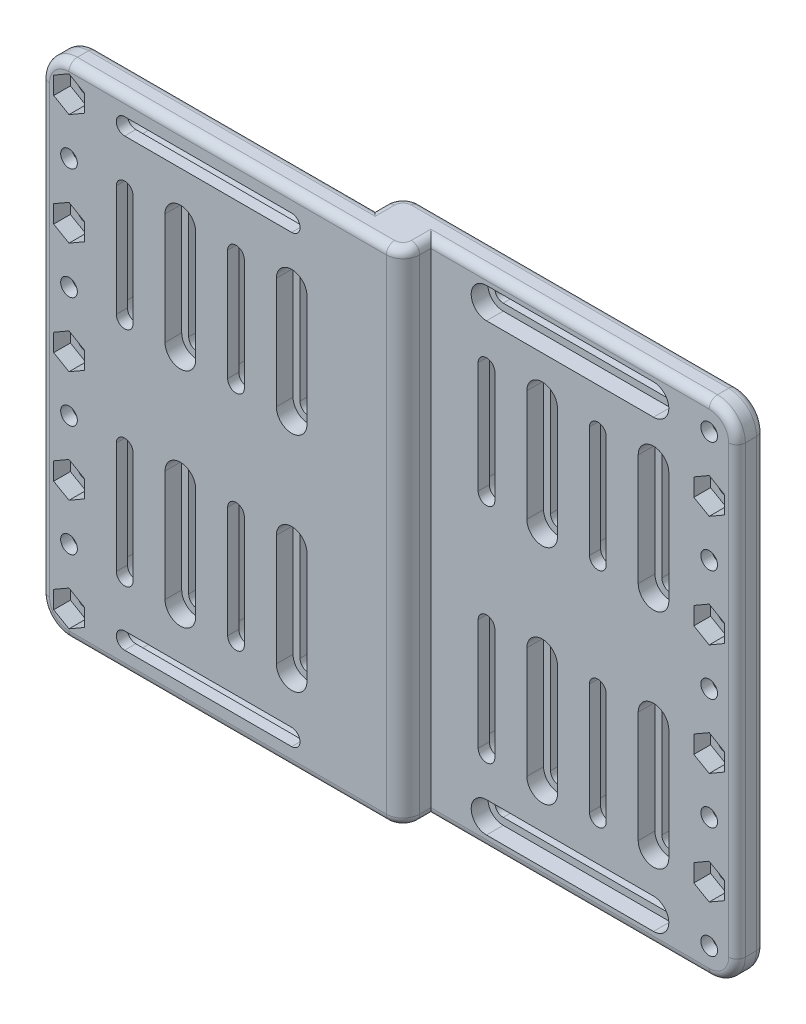
SolidWorks part; units mm, degrees
ref_plane "Front Plane" through (0, 0, 0) normal (0, 0, 1) x (1, 0, 0)
ref_plane "Top Plane" through (0, 0, 0) normal (0, 1, 0) x (1, 0, 0)
ref_plane "Right Plane" through (0, 0, 0) normal (1, 0, 0) x (0, 0, -1)
sketch "草图1" plane through (0, 0, 0) normal (0, 0, 1) x (1, 0, 0)
  line L2 (0, 45) -> (0, -45) construction
  circle A0 centre (0, 0) radius 45 construction
  dimension "D1" = 90
sketch "草图2" plane through (0, 0, 0) normal (0, 0, 1) x (1, 0, 0)
  line L0 (0, 45) -> (5, 45)
  line L1 (0, 45) -> (-60, 45)
  line L2 (0, 45) -> (0, -45) construction
  line L3 (0, -45) -> (-60, -45)
  line L4 (-60, 45) -> (-60, -45)
  line L5 (5, 45) -> (5, -45)
  line L6 (5, -45) -> (0, -45)
  dimension "D1" = 60
  dimension "D2" = 5
extrude "凸台-拉伸2" add sketch "草图2" along normal blind 5
sketch "草图3" plane through (0, 0, 0) normal (0, 0, -1) x (-1, 0, 0)
  line L0 (0, 45) -> (5, 45)
  line L1 (0, 45) -> (-60, 45)
  line L2 (0, 45) -> (0, -45) construction
  line L3 (0, -45) -> (-60, -45)
  line L4 (-60, 45) -> (-60, -45)
  line L5 (-5, 45) -> (60, 45) construction
  line L6 (5, 45) -> (5, -45)
  line L7 (60, -45) -> (-5, -45) construction
  line L8 (5, -45) -> (0, -45)
  dimension "D1" = 60
  dimension "D2" = 5
extrude "凸台-拉伸3" add sketch "草图3" along normal blind 5
sketch "草图4" plane through (0, 0, -5) normal (0, 0, -1) x (-1, 0, 0)
  line L0 (-60, 45) -> (-60, -45) construction
  circle A0 centre (-55, 0) radius 1.5
  dimension "D2" = 3
  dimension "D1" = 5
sketch "草图5" plane through (0, 0, -5) normal (0, 0, -1) x (-1, 0, 0)
  line L1 (-55, -3.1754) -> (-52.25, -1.5877)
  line L2 (-52.25, -1.5877) -> (-52.25, 1.5877)
  line L3 (-52.25, 1.5877) -> (-55, 3.1754)
  line L4 (-55, 3.1754) -> (-57.75, 1.5877)
  line L5 (-57.75, 1.5877) -> (-57.75, -1.5877)
  line L6 (-57.75, -1.5877) -> (-55, -3.1754)
  circle A1 centre (-55, 0) radius 2.75 construction
  dimension "D1" = 5.5
extrude "切除-拉伸1" cut sketch "草图4" against normal through all
extrude "切除-拉伸2" cut sketch "草图5" against normal blind 3
sketch "草图6" plane through (0, 0, 5) normal (0, 0, 1) x (1, 0, 0)
  line L0 (-60, 45) -> (-60, -45) construction
  circle A0 centre (-55, 0) radius 1.5
  dimension "D1" = 3
  dimension "D2" = 5
sketch "草图7" plane through (0, 0, 5) normal (0, 0, 1) x (1, 0, 0)
  line L1 (-55, 3.1754) -> (-57.75, 1.5877)
  line L2 (-57.75, 1.5877) -> (-57.75, -1.5877)
  line L3 (-57.75, -1.5877) -> (-55, -3.1754)
  line L4 (-55, -3.1754) -> (-52.25, -1.5877)
  line L5 (-52.25, -1.5877) -> (-52.25, 1.5877)
  line L6 (-52.25, 1.5877) -> (-55, 3.1754)
  circle A1 centre (-55, 0) radius 2.75 construction
  dimension "D1" = 5.5
extrude "切除-拉伸3" cut sketch "草图6" against normal through all
extrude "切除-拉伸4" cut sketch "草图7" against normal blind 3
pattern_linear "阵列(线性)1" count 5 spacing 10 along (0, -1, 0) count 5 spacing 10 along (0, 1, 0) of "切除-拉伸1"
pattern_linear "阵列(线性)2" count 5 spacing 10 along (0, -1, 0) count 5 spacing 10 along (0, 1, 0) of "切除-拉伸3"
pattern_linear "阵列(线性)9" count 3 spacing 20 along (0, 1, 0) count 3 spacing 20 along (0, -1, 0) of "切除-拉伸2"
pattern_linear "阵列(线性)10" count 3 spacing 20 along (0, 1, 0) count 3 spacing 20 along (0, -1, 0) of "切除-拉伸4"
sketch "草图19" plane through (0, 0, 0) normal (0, 0, 1) x (1, 0, 0)
  line L1 (55, 13.1754) -> (52.25, 11.5877)
  line L2 (52.25, 11.5877) -> (52.25, 8.4123)
  line L3 (52.25, 8.4123) -> (55, 6.8246)
  line L4 (55, 6.8246) -> (57.75, 8.4123)
  line L5 (57.75, 8.4123) -> (57.75, 11.5877)
  line L6 (57.75, 11.5877) -> (55, 13.1754)
  circle A0 centre (55, 10) radius 2.75 construction
  dimension "D1" = 5.5
extrude "切除-拉伸15" cut sketch "草图19" against normal blind 3
sketch "草图20" plane through (0, 0, 0) normal (0, 0, -1) x (-1, 0, 0)
  line L1 (55, 6.8246) -> (57.75, 8.4123)
  line L2 (57.75, 8.4123) -> (57.75, 11.5877)
  line L3 (57.75, 11.5877) -> (55, 13.1754)
  line L4 (55, 13.1754) -> (52.25, 11.5877)
  line L5 (52.25, 11.5877) -> (52.25, 8.4123)
  line L6 (52.25, 8.4123) -> (55, 6.8246)
  circle A0 centre (55, 10) radius 2.75 construction
  dimension "D1" = 5.5
extrude "切除-拉伸16" cut sketch "草图20" against normal blind 3
pattern_linear "阵列(线性)11" count 3 spacing 20 along (0, -1, 0) count 3 spacing 20 along (0, 1, 0) of "切除-拉伸15"
pattern_linear "阵列(线性)12" count 3 spacing 20 along (0, -1, 0) count 3 spacing 20 along (0, 1, 0) of "切除-拉伸16"
sketch "草图8" plane through (0, 0, 0) normal (0, 0, 1) x (1, 0, 0)
  line L0 (-45, -997.8304) -> (-45, 49002.1696) construction
  line L1 (45, -998.9875) -> (45, 49001.0125) construction
  line L2 (-1000, 0) -> (49000, 0) construction
  line L3 (0, 45) -> (0, -45) construction
  line L4 (0, -1000) -> (0, 49000) construction
  point P9 (0, 0)
  dimension "D1" = 90
  dimension "D2" = 45
sketch "草图9" plane through (0, 0, 0) normal (0, 0, -1) x (-1, 0, 0)
  line L0 (-1000, 0) -> (49000, 0) construction
  line L1 (0, 45) -> (0, -45) construction
  line L2 (15, 40) -> (45, 40) construction
  line L3 (15, 41.5) -> (45, 41.5)
  line L4 (15, 38.5) -> (45, 38.5)
  line L5 (15, -40) -> (45, -40) construction
  line L6 (15, -41.5) -> (45, -41.5)
  line L7 (15, -38.5) -> (45, -38.5)
  line L8 (60, 45) -> (60, -45) construction
  arc A0 (15, 41.5) -> (15, 38.5) centre (15, 40) ccw
  arc A1 (45, 38.5) -> (45, 41.5) centre (45, 40) ccw
  arc A2 (15, -41.5) -> (15, -38.5) centre (15, -40) cw
  arc A3 (45, -38.5) -> (45, -41.5) centre (45, -40) cw
  point P5 (0, 0)
  point P7 (30, 40)
  point P14 (30, -40)
  dimension "D1" = 3
  dimension "D2" = 15
  dimension "D3" = 30
  dimension "D4" = 80
sketch "草图10" plane through (0, 0, 0) normal (0, 0, 1) x (1, 0, 0)
  line L0 (-1015.4001, 0) -> (48984.5999, 0) construction
  line L2 (15, 40) -> (45, 40) construction
  line L3 (15, 41.5) -> (45, 41.5)
  line L4 (15, 38.5) -> (45, 38.5)
  line L5 (15, -40) -> (45, -40) construction
  line L6 (15, -41.5) -> (45, -41.5)
  line L7 (15, -38.5) -> (45, -38.5)
  line L9 (60, 45) -> (60, -45) construction
  arc A0 (15, 41.5) -> (15, 38.5) centre (15, 40) ccw
  arc A1 (45, 38.5) -> (45, 41.5) centre (45, 40) ccw
  arc A2 (15, -41.5) -> (15, -38.5) centre (15, -40) cw
  arc A3 (45, -38.5) -> (45, -41.5) centre (45, -40) cw
  point P7 (30, 40)
  point P14 (30, -40)
  dimension "D1" = 3
  dimension "D2" = 15
  dimension "D3" = 30
  dimension "D4" = 80
sketch "草图11" plane through (0, 0, 0) normal (0, 0, -1) x (-1, 0, 0)
  line L0 (15, 40) -> (45, 40) construction
  line L1 (15, 42.75) -> (45, 42.75)
  line L2 (15, 37.25) -> (45, 37.25)
  line L3 (15, -40) -> (45, -40) construction
  line L4 (15, -37.25) -> (45, -37.25)
  line L5 (15, -42.75) -> (45, -42.75)
  arc A0 (15, 42.75) -> (15, 37.25) centre (15, 40) ccw
  arc A1 (45, 37.25) -> (45, 42.75) centre (45, 40) ccw
  arc A2 (15, -37.25) -> (15, -42.75) centre (15, -40) ccw
  arc A3 (45, -42.75) -> (45, -37.25) centre (45, -40) ccw
  point P4 (30, 40)
  point P9 (30, -40)
  dimension "D1" = 5.5
  dimension "D2" = 5.5
sketch "草图12" plane through (0, 0, 0) normal (0, 0, 1) x (1, 0, 0)
  line L0 (15, 40) -> (45, 40) construction
  line L3 (15, 42.75) -> (45, 42.75)
  line L4 (15, 37.25) -> (45, 37.25)
  line L5 (15, -40) -> (45, -40) construction
  line L6 (15, -37.25) -> (45, -37.25)
  line L7 (15, -42.75) -> (45, -42.75)
  arc A3 (15, 42.75) -> (15, 37.25) centre (15, 40) ccw
  arc A4 (45, 37.25) -> (45, 42.75) centre (45, 40) ccw
  arc A5 (15, -37.25) -> (15, -42.75) centre (15, -40) ccw
  arc A6 (45, -42.75) -> (45, -37.25) centre (45, -40) ccw
  point P2 (30, 40)
  point P7 (30, -40)
  dimension "D1" = 5.5
  dimension "D2" = 5.5
extrude "切除-拉伸5" cut sketch "草图9" against normal through all
extrude "切除-拉伸6" cut sketch "草图11" against normal blind 3
extrude "切除-拉伸7" cut sketch "草图10" against normal through all
extrude "切除-拉伸8" cut sketch "草图12" against normal blind 3
sketch "草图13" plane through (0, 0, 0) normal (0, 0, -1) x (-1, 0, 0)
  line L0 (15, 30) -> (15, 10) construction
  line L1 (16.5, 30) -> (16.5, 10)
  line L2 (13.5, 30) -> (13.5, 10)
  line L3 (-1000, 0) -> (49000, 0) construction
  line L4 (15, -30) -> (15, -10) construction
  line L5 (16.5, -30) -> (16.5, -10)
  line L6 (13.5, -30) -> (13.5, -10)
  line L7 (15, 10) -> (15, -10) construction
  line L8 (60, 45) -> (60, -45) construction
  arc A0 (16.5, 30) -> (13.5, 30) centre (15, 30) ccw
  arc A1 (13.5, 10) -> (16.5, 10) centre (15, 10) ccw
  arc A2 (16.5, -30) -> (13.5, -30) centre (15, -30) cw
  arc A3 (13.5, -10) -> (16.5, -10) centre (15, -10) cw
  point P2 (15, 20)
  point P12 (15, -20)
  dimension "D1" = 3
  dimension "D2" = 20
  dimension "D3" = 60
  dimension "D4" = 45
sketch "草图14" plane through (0, 0, 0) normal (0, 0, 1) x (1, 0, 0)
  line L0 (-1000, 0) -> (49000, 0) construction
  line L2 (15, 10) -> (15, 30) construction
  line L3 (13.5, 10) -> (13.5, 30)
  line L4 (16.5, 10) -> (16.5, 30)
  line L5 (15, -10) -> (15, -30) construction
  line L6 (13.5, -10) -> (13.5, -30)
  line L7 (16.5, -10) -> (16.5, -30)
  line L8 (15, 10) -> (15, -10) construction
  line L9 (60, 45) -> (60, -45) construction
  arc A0 (13.5, 10) -> (16.5, 10) centre (15, 10) ccw
  arc A1 (16.5, 30) -> (13.5, 30) centre (15, 30) ccw
  arc A2 (13.5, -10) -> (16.5, -10) centre (15, -10) cw
  arc A3 (16.5, -30) -> (13.5, -30) centre (15, -30) cw
  point P5 (15, 20)
  point P12 (15, -20)
  dimension "D1" = 20
  dimension "D2" = 60
  dimension "D3" = 3
  dimension "D4" = 45
extrude "切除-拉伸9" cut sketch "草图13" against normal through all
extrude "切除-拉伸10" cut sketch "草图14" against normal through all
pattern_linear "阵列(线性)3" count 4 spacing 10 along (-1, 0, 0) of "切除-拉伸9"
pattern_linear "阵列(线性)4" count 4 spacing 10 along (1, 0, 0) of "切除-拉伸10"
sketch "草图15" plane through (0, 0, 0) normal (0, 0, -1) x (-1, 0, 0)
  line L0 (45, 30) -> (45, 10) construction
  line L1 (47.75, 30) -> (47.75, 10)
  line L2 (42.25, 30) -> (42.25, 10)
  line L3 (45, -10) -> (45, -30) construction
  line L4 (47.75, -10) -> (47.75, -30)
  line L5 (42.25, -10) -> (42.25, -30)
  arc A0 (47.75, 30) -> (42.25, 30) centre (45, 30) ccw
  arc A1 (42.25, 10) -> (47.75, 10) centre (45, 10) ccw
  arc A2 (47.75, -10) -> (42.25, -10) centre (45, -10) ccw
  arc A3 (42.25, -30) -> (47.75, -30) centre (45, -30) ccw
  point P4 (45, 20)
  point P9 (45, -20)
  dimension "D1" = 5.5
  dimension "D2" = 5.5
extrude "切除-拉伸11" cut sketch "草图15" against normal blind 3
sketch "草图16" plane through (0, 0, 5) normal (0, 0, 1) x (1, 0, 0)
  line L0 (-15, 30) -> (-15, 10) construction
  line L3 (-12.25, 30) -> (-12.25, 10)
  line L6 (-17.75, 30) -> (-17.75, 10)
  line L7 (-15, -10) -> (-15, -30) construction
  line L8 (-12.25, -10) -> (-12.25, -30)
  line L9 (-17.75, -10) -> (-17.75, -30)
  arc A4 (-12.25, 30) -> (-17.75, 30) centre (-15, 30) ccw
  arc A5 (-17.75, 10) -> (-12.25, 10) centre (-15, 10) ccw
  arc A6 (-12.25, -10) -> (-17.75, -10) centre (-15, -10) ccw
  arc A7 (-17.75, -30) -> (-12.25, -30) centre (-15, -30) ccw
  point P4 (-15, 20)
  point P9 (-15, -20)
  dimension "D1" = 5.5
  dimension "D2" = 5.5
extrude "切除-拉伸12" cut sketch "草图16" against normal blind 3
pattern_linear "阵列(线性)6" count 2 spacing 20 along (-1, 0, 0) of "切除-拉伸12"
pattern_linear "阵列(线性)13" count 2 spacing 20 along (1, 0, 0) of "切除-拉伸11"
sketch "草图17" plane through (0, 0, 0) normal (0, 0, 1) x (1, 0, 0)
  line L0 (45, 30) -> (45, 10) construction
  line L1 (47.75, 30) -> (47.75, 10)
  line L2 (42.25, 30) -> (42.25, 10)
  line L3 (45, -10) -> (45, -30) construction
  line L6 (47.75, -10) -> (47.75, -30)
  line L7 (42.25, -10) -> (42.25, -30)
  arc A0 (47.75, 30) -> (42.25, 30) centre (45, 30) ccw
  arc A1 (42.25, 10) -> (47.75, 10) centre (45, 10) ccw
  arc A4 (47.75, -10) -> (42.25, -10) centre (45, -10) ccw
  arc A5 (42.25, -30) -> (47.75, -30) centre (45, -30) ccw
  point P4 (45, 20)
  point P11 (45, -20)
  dimension "D1" = 5.5
  dimension "D2" = 5.5
extrude "切除-拉伸13" cut sketch "草图17" against normal blind 3
sketch "草图18" plane through (0, 0, -5) normal (0, 0, -1) x (-1, 0, 0)
  line L0 (-15, 30) -> (-15, 10) construction
  line L3 (-12.25, 30) -> (-12.25, 10)
  line L6 (-17.75, 30) -> (-17.75, 10)
  line L7 (-15, -10) -> (-15, -30) construction
  line L8 (-12.25, -10) -> (-12.25, -30)
  line L9 (-17.75, -10) -> (-17.75, -30)
  arc A4 (-12.25, 30) -> (-17.75, 30) centre (-15, 30) ccw
  arc A5 (-17.75, 10) -> (-12.25, 10) centre (-15, 10) ccw
  arc A6 (-12.25, -10) -> (-17.75, -10) centre (-15, -10) ccw
  arc A7 (-17.75, -30) -> (-12.25, -30) centre (-15, -30) ccw
  point P4 (-15, 20)
  point P9 (-15, -20)
  dimension "D1" = 5.5
  dimension "D2" = 5.5
extrude "切除-拉伸14" cut sketch "草图18" against normal blind 3
pattern_linear "阵列(线性)8" count 2 spacing 20 along (1, 0, 0) of "切除-拉伸14"
pattern_linear "阵列(线性)14" count 2 spacing 20 along (-1, 0, 0) of "切除-拉伸13"
fillet "圆角2" radius 3 2 edges at (-5, 0, -5) (5, 0, 5)
fillet "圆角3" radius 5 4 edges at (60, 45, -2.5) (-60, 45, 2.5) (-60, -45, 2.5) (60, -45, -2.5)
fillet "圆角4" radius 1.5 28 edges at (30, 45, 0) (58.5355, 43.5355, 0) (60, 0, 0) (58.5355, -43.5355, 0) (5, 45, 1) (4.1213, 45, 4.1213) (-26.5, 45, 5) (-58.5355, 43.5355, 5) (-60, 0, 5) (-58.5355, -43.5355, 5) (5, -45, 1) (4.1213, -45, 4.1213) (-30, 45, 0) (-58.5355, 43.5355, 0) (-60, 0, 0) (-58.5355, -43.5355, 0) (-5, 45, -1) (-4.1213, 45, -4.1213) (26.5, 45, -5) (58.5355, 43.5355, -5) (60, 0, -5) (58.5355, -43.5355, -5) (-5, -45, -1) (-4.1213, -45, -4.1213) (30, -45, 0) (-26.5, -45, 5) (-30, -45, 0) (26.5, -45, -5)
